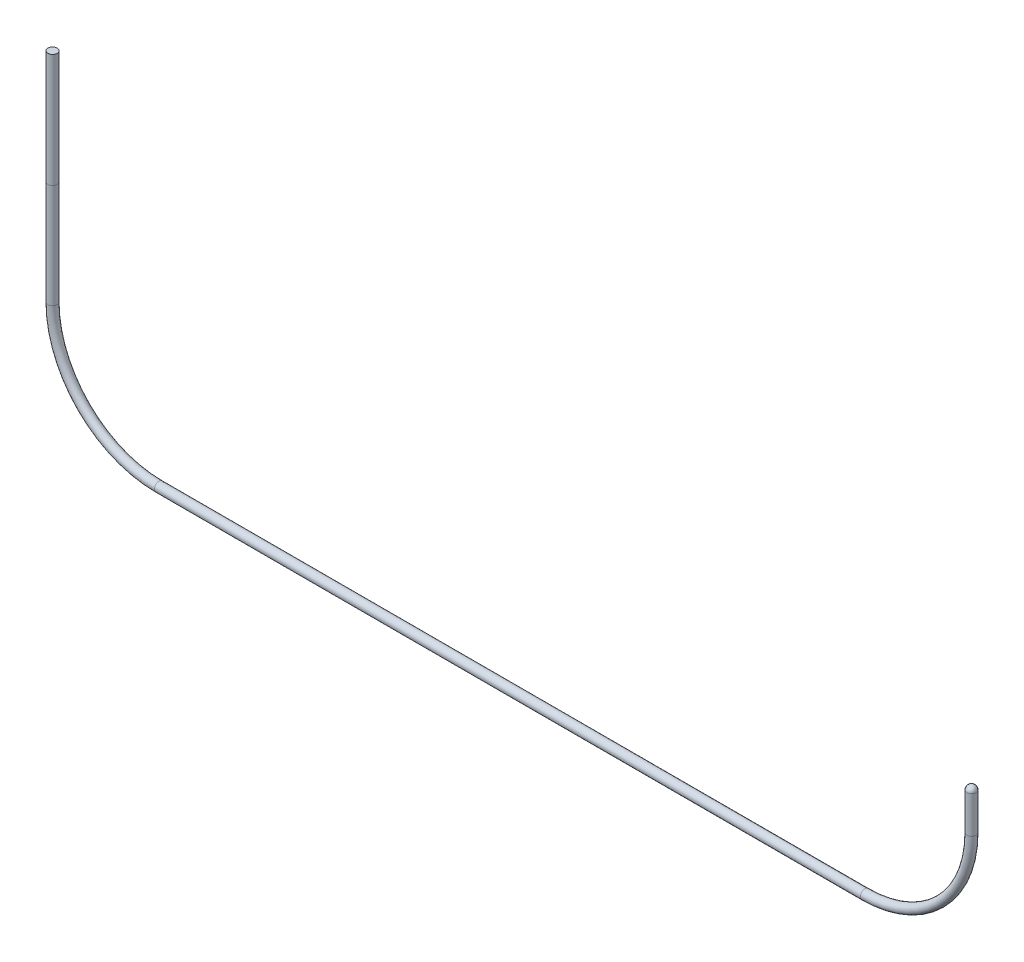
SolidWorks part; units mm, degrees
ref_plane "Front" through (0, 0, 0) normal (0, 0, 1) x (1, 0, 0)
ref_plane "Top" through (0, 0, 0) normal (0, 1, 0) x (1, 0, 0)
ref_plane "Right" through (0, 0, 0) normal (1, 0, 0) x (0, 0, -1)
sketch "Sketch2" plane through (0, 0, 0) normal (0, 0, 1) x (1, 0, 0)
  line L0 (16.5989, -3.4925) -> (16.5989, -2.0066)
  line L2 (-16.5989, 4.2926) -> (-16.5989, -3.4925)
  line L3 (-12.6238, -7.4676) -> (12.6238, -7.4676)
  arc A1 (-16.5989, -3.4925) -> (-12.6238, -7.4676) centre (-12.6238, -3.4925) ccw
  arc A2 (12.6238, -7.4676) -> (16.5989, -3.4925) centre (12.6238, -3.4925) ccw
  dimension "D1" = 3.9751
  dimension "D2" = 3.9751
  dimension "D5" = 12.6238
  dimension "D3" = 4.2926
  dimension "D4" = 7.4676
  dimension "D6" = 2.0066
  dimension "D7" = 12.6238
ref_plane "Plane1" through (0, 4.2926, 0) normal (0, 1, 0) x (-1, 0, 0)
sketch "Sketch3" plane through (0, 4.2926, 0) normal (0, 1, 0) x (-1, 0, 0)
  line L0 (6.4681, 0) -> (-6.4681, 0) construction
  circle A0 centre (16.4338, 0) radius 0.1651
  dimension "D1" = 0.3302
sweep "Sweep1" add profiles "Sketch3" path "Sketch2"
fillet "Fillet1" radius 0.1651 1 edges at (16.4338, -2.0066, 0.1651)
sketch "Sketch6" plane through (0, 0, 0) normal (0, 0, 1) x (1, 0, 0)
  line L1 (-19.4945, 0.2286) -> (19.4183, 0.2286)
  dimension "D1" = 0.2286
split line "Split Line2"
sketch "Sketch4" plane through (0, 0, 0) normal (0, 0, 1) x (1, 0, 0)
  line L0 (-16.4338, 0.2286) -> (-16.4338, -3.4925)
  line L3 (-12.6238, -7.3025) -> (12.6238, -7.3025)
  line L4 (-12.6238, -7.1374) -> (-12.6238, -7.4676) construction
  line L5 (12.6238, -7.1374) -> (12.6238, -7.4676) construction
  line L9 (-16.5989, 0.2286) -> (-16.2687, 0.2286) construction
  line L10 (16.4338, -3.4925) -> (16.4338, -2.0066)
  arc A2 (-16.4338, -3.4925) -> (-12.6238, -7.3025) centre (-12.6238, -3.4925) ccw
  arc A3 (-16.4338, -3.4925) -> (-12.6238, -7.3025) centre (-12.6238, -3.4925) ccw
  arc A4 (16.5989, -2.1717) -> (16.2687, -2.1717) centre (16.4338, -2.1717) ccw construction
  arc A5 (12.6238, -7.3025) -> (16.4338, -3.4925) centre (12.6238, -3.4925) ccw
  arc A6 (12.6238, -7.3025) -> (16.4338, -3.4925) centre (12.6238, -3.4925) ccw
  dimension "D1" = 0.1651
  dimension "D2" = 0.1651
